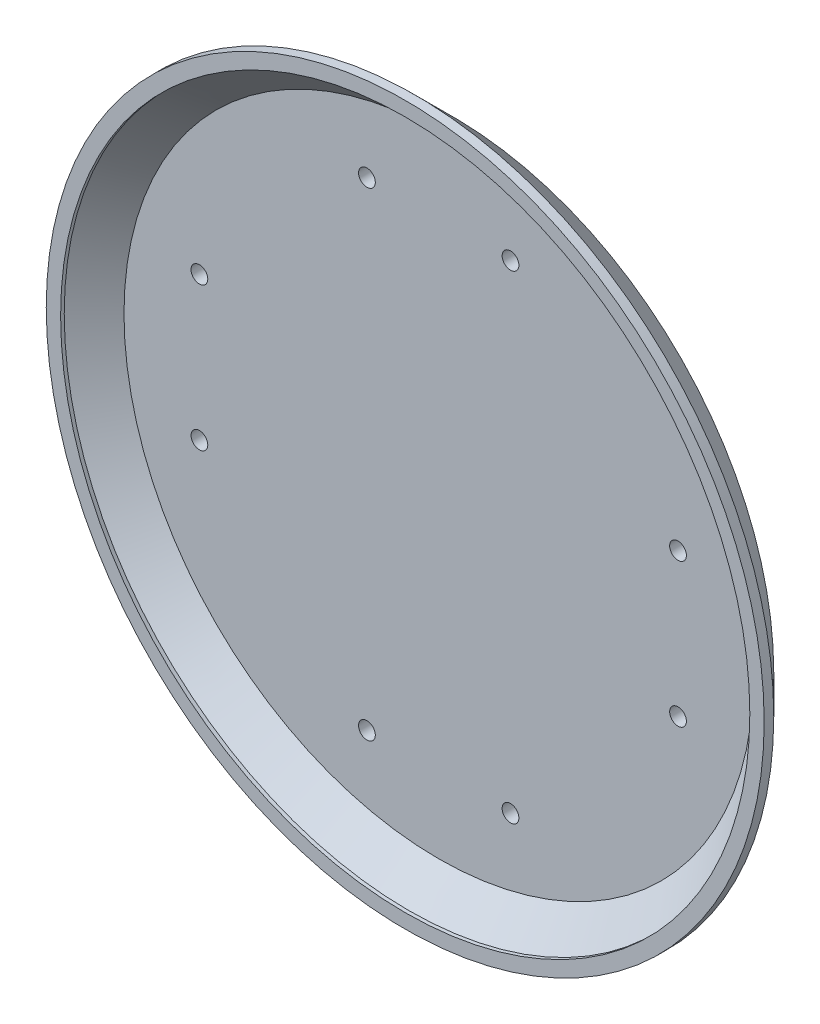
SolidWorks part; units mm, degrees
ref_plane "Front Plane" through (0, 0, 0) normal (0, 0, 1) x (1, 0, 0)
ref_plane "Top Plane" through (0, 0, 0) normal (0, 1, 0) x (1, 0, 0)
ref_plane "Right Plane" through (0, 0, 0) normal (1, 0, 0) x (0, 0, -1)
sketch "Sketch1" plane through (0, 0, 0) normal (0, 0, 1) x (1, 0, 0)
  circle A0 centre (0, 0) radius 75
  dimension "D1" = 150
extrude "Boss-Extrude1" add sketch "Sketch1" along normal blind 10
chamfer "Chamfer1" distance 8 angle 45 1 edges at (75, 0, 0)
shell "Shell1" thickness 3
sketch "Sketch2" plane through (0, 0, 0) normal (0, 0, -1) x (-1, 0, 0)
  line L1 (-50, 15) -> (50, 15) construction
  line L2 (-50, 15) -> (-50, -15) construction
  line L3 (-50, -15) -> (50, -15) construction
  line L4 (50, 15) -> (50, -15) construction
  line L5 (-50, 15) -> (50, -15) construction
  line L6 (-50, -15) -> (50, 15) construction
  line L7 (-15, 50) -> (15, 50) construction
  line L8 (-15, 50) -> (-15, -50) construction
  line L9 (-15, -50) -> (15, -50) construction
  line L10 (15, 50) -> (15, -50) construction
  line L11 (-15, 50) -> (15, -50) construction
  line L12 (-15, -50) -> (15, 50) construction
  circle A0 centre (-50, 15) radius 1.75
  circle A1 centre (-50, -15) radius 1.75
  circle A2 centre (-15, -50) radius 1.75
  circle A3 centre (15, -50) radius 1.75
  circle A4 centre (50, -15) radius 1.75
  circle A5 centre (50, 15) radius 1.75
  circle A6 centre (-15, 50) radius 1.75
  circle A7 centre (15, 50) radius 1.75
  point P0 (0, 0)
  point P6 (0, 0)
  dimension "D3" = 3.5
  dimension "D1" = 100
  dimension "D2" = 30
extrude "Cut-Extrude1" cut sketch "Sketch2" against normal through all
